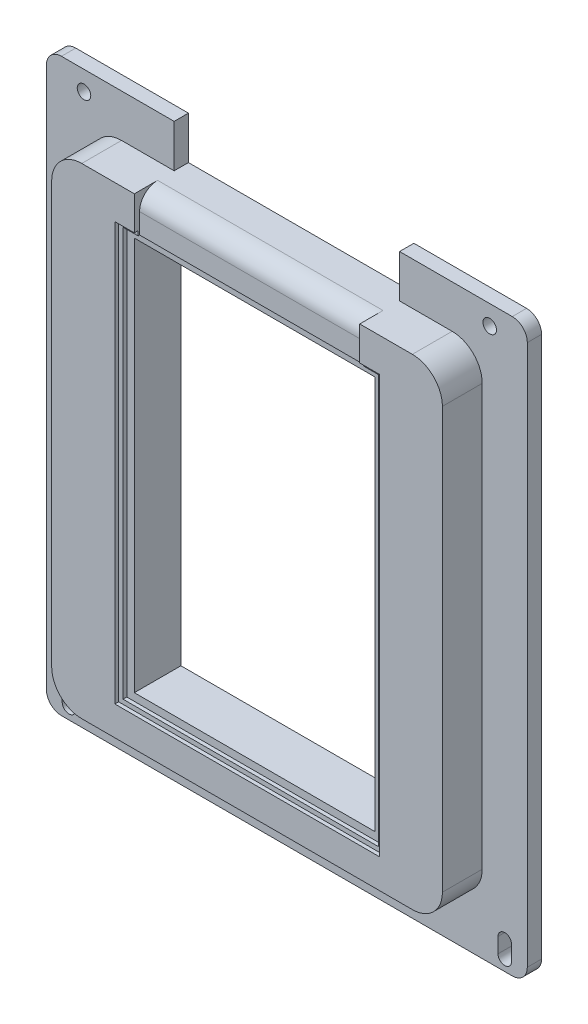
SolidWorks part; units mm, degrees
ref_plane "Front" through (0, 0, 0) normal (0, 0, 1) x (1, 0, 0)
ref_plane "Top" through (0, 0, 0) normal (0, 1, 0) x (1, 0, 0)
ref_plane "Right" through (0, 0, 0) normal (1, 0, 0) x (0, 0, -1)
sketch "Sketch1" plane through (0, 0, 0) normal (0, 0, 1) x (1, 0, 0)
  line L1 (-80, -95) -> (80, -95)
  line L2 (-80, -95) -> (-80, 95)
  line L3 (-80, 95) -> (80, 95)
  line L4 (80, -95) -> (80, 95)
  line L5 (-80, -95) -> (80, 95) construction
  line L6 (-80, 95) -> (80, -95) construction
  point P0 (0, 0)
  dimension "D1" = 160
  dimension "D2" = 190
extrude "Boss-Extrude1" add sketch "Sketch1" along normal blind 18
sketch "Sketch3" plane through (0, 0, 18) normal (0, 0, 1) x (1, 0, 0)
  line L0 (80, -95) -> (80, 95) construction
  line L1 (-80, 95) -> (80, 95)
  line L2 (-80, 95) -> (-80, 80.75)
  line L3 (-80, 80.75) -> (80, 80.75)
  line L4 (80, 95) -> (80, 80.75)
  dimension "D1" = 14.25
extrude "Cut-Extrude2" cut sketch "Sketch3" against normal blind 13.25
sketch "Sketch4" plane through (0, 0, 18) normal (0, 0, 1) x (1, 0, 0)
  line L0 (80, -95) -> (80, 80.75) construction
  line L1 (-80, -95) -> (80, -95)
  line L2 (-80, -95) -> (-80, -79.25)
  line L3 (-80, -79.25) -> (80, -79.25)
  line L4 (80, -95) -> (80, -79.25)
  dimension "D1" = 15.75
extrude "Cut-Extrude3" cut sketch "Sketch4" against normal blind 13.25
sketch "Sketch2" plane through (0, 0, 0) normal (0, 0, -1) x (-1, 0, 0)
  line L0 (-67.5, 88.5) -> (67.5, 88.5) construction
  line L1 (67.5, 88.5) -> (67.5, -88.5) construction
  line L2 (67.5, -88.5) -> (-67.5, -88.5) construction
  line L3 (-67.5, -88.5) -> (-67.5, 88.5) construction
  line L4 (72.5, -88.5) -> (67.5, -88.5) construction
  line L5 (-67.5, -88.5) -> (-72.5, -88.5) construction
  circle A0 centre (-67.5, 88.5) radius 2.25
  circle A1 centre (67.5, 88.5) radius 2.25
  circle A4 centre (-72.5, -88.5) radius 2.25
  circle A5 centre (72.5, -88.5) radius 2.25
  point P8 (-67.5, 0)
  point P9 (0, 88.5)
  dimension "D2" = 4.5
  dimension "D1" = 135
  dimension "D3" = 177
  dimension "D4" = 145
extrude "Cut-Extrude1" cut sketch "Sketch2" against normal through all
sketch "Sketch5" plane through (0, 0, 18) normal (0, 0, 1) x (1, 0, 0)
  line L1 (-40, -65.5) -> (40, -65.5)
  line L2 (-40, -65.5) -> (-40, 65.5)
  line L3 (-40, 65.5) -> (40, 65.5)
  line L4 (40, -65.5) -> (40, 65.5)
  line L5 (-40, -65.5) -> (40, 65.5) construction
  line L6 (-40, 65.5) -> (40, -65.5) construction
  point P0 (0, 0)
  dimension "D1" = 80
  dimension "D2" = 131
extrude "Cut-Extrude4" cut sketch "Sketch5" against normal through all
sketch "Sketch6" plane through (0, 0, 18) normal (0, 0, 1) x (1, 0, 0)
  line L1 (-42.5, -68) -> (42.5, -68)
  line L2 (-42.5, -68) -> (-42.5, 68)
  line L3 (-42.5, 68) -> (42.5, 68)
  line L4 (42.5, -68) -> (42.5, 68)
  line L5 (-42.5, -68) -> (42.5, 68) construction
  line L6 (-42.5, 68) -> (42.5, -68) construction
  point P0 (0, 0)
  dimension "D1" = 85
  dimension "D2" = 136
extrude "Cut-Extrude5" cut sketch "Sketch6" against normal blind 2.5
sketch "Sketch7" plane through (0, 0, 18) normal (0, 0, 1) x (1, 0, 0)
  line L0 (42.5, 68) -> (-42.5, 68) construction
  line L1 (-37.5, 68) -> (37.5, 68)
  line L2 (-37.5, 68) -> (-37.5, 80.75)
  line L3 (-37.5, 80.75) -> (37.5, 80.75)
  line L4 (37.5, 68) -> (37.5, 80.75)
  line L5 (-80, 80.75) -> (80, 80.75) construction
  point P8 (0, 68)
  dimension "D1" = 75
extrude "Cut-Extrude6" cut sketch "Sketch7" against normal offset from surface (1.75 mm away) 0.75 up to face at (0, 0, 15.5)
sketch "Sketch8" plane through (0, 0, 18) normal (0, 0, 1) x (1, 0, 0)
  line L1 (-44, -69.5) -> (44, -69.5)
  line L2 (-44, -69.5) -> (-44, 69.5)
  line L3 (-44, 69.5) -> (44, 69.5)
  line L4 (44, -69.5) -> (44, 69.5)
  point P4 (0, 69.5)
  point P6 (-44, 0)
  dimension "D1" = 88
  dimension "D2" = 139
extrude "Cut-Extrude7" cut sketch "Sketch8" against normal offset from surface (1.25 mm away) 1.25 contours L3 L4 L1 L2 up to face at (0, 0, 15.5)
sketch "Sketch9" plane through (0, 0, 4.75) normal (0, 0, 1) x (1, 0, 0)
  line L0 (80, 95) -> (-80, 95) construction
  line L1 (-37.5, 95) -> (37.5, 95)
  line L2 (-37.5, 95) -> (-37.5, 80.75)
  line L3 (-37.5, 80.75) -> (37.5, 80.75)
  line L4 (37.5, 95) -> (37.5, 80.75)
  line L5 (-80, 80.75) -> (80, 80.75) construction
  line L6 (37.5, 68) -> (37.5, 80.75) construction
  line L8 (-37.5, 80.75) -> (-37.5, 69.5) construction
extrude "Cut-Extrude8" cut sketch "Sketch9" against normal through all
fillet "Fillet1" radius 6 1 edges at (0, 80.75, 16.25)
sketch "Sketch10" plane through (0, 0, 18) normal (0, 0, 1) x (1, 0, 0)
  line L0 (80, -79.25) -> (-80, -79.25) construction
  line L1 (80, 80.75) -> (65, 80.75)
  line L2 (80, 80.75) -> (80, -79.25)
  line L3 (80, -79.25) -> (65, -79.25)
  line L4 (65, 80.75) -> (65, -79.25)
  line L6 (-80, 80.75) -> (-65, 80.75)
  line L7 (-80, 80.75) -> (-80, -79.25)
  line L8 (-80, -79.25) -> (-65, -79.25)
  line L9 (-65, 80.75) -> (-65, -79.25)
  dimension "D1" = 15
extrude "Cut-Extrude9" cut sketch "Sketch10" against normal up to surface (13.25 mm away) up to face at (-74.75, -88.5, 4.75)
sketch "Sketch11" plane through (0, 0, 0) normal (0, 0, -1) x (-1, 0, 0)
  line L0 (-72.5, -91) -> (-72.5, -86) construction
  line L1 (-74.75, -91) -> (-74.75, -86)
  line L2 (-70.25, -91) -> (-70.25, -86)
  line L3 (72.5, -91) -> (72.5, -86) construction
  line L4 (70.25, -91) -> (70.25, -86)
  line L5 (74.75, -91) -> (74.75, -86)
  arc A0 (-74.75, -91) -> (-70.25, -91) centre (-72.5, -91) ccw
  arc A1 (-70.25, -86) -> (-74.75, -86) centre (-72.5, -86) ccw
  circle A2 centre (-72.5, -88.5) radius 2.25 construction
  arc A3 (70.25, -91) -> (74.75, -91) centre (72.5, -91) ccw
  arc A4 (74.75, -86) -> (70.25, -86) centre (72.5, -86) ccw
  circle A5 centre (72.5, -88.5) radius 2.25 construction
  point P2 (-72.5, -88.5)
  point P12 (72.5, -88.5)
  dimension "D1" = 5
extrude "Cut-Extrude10" cut sketch "Sketch11" against normal through all
fillet "Fillet2" radius 10 4 edges at (-65, -79.25, 11.375) (-65, 80.75, 11.375) (65, -79.25, 11.375) (65, 80.75, 11.375)
fillet "Fillet3" radius 5 4 edges at (80, -95, 2.375) (-80, -95, 2.375) (80, 95, 2.375) (-80, 95, 2.375)
